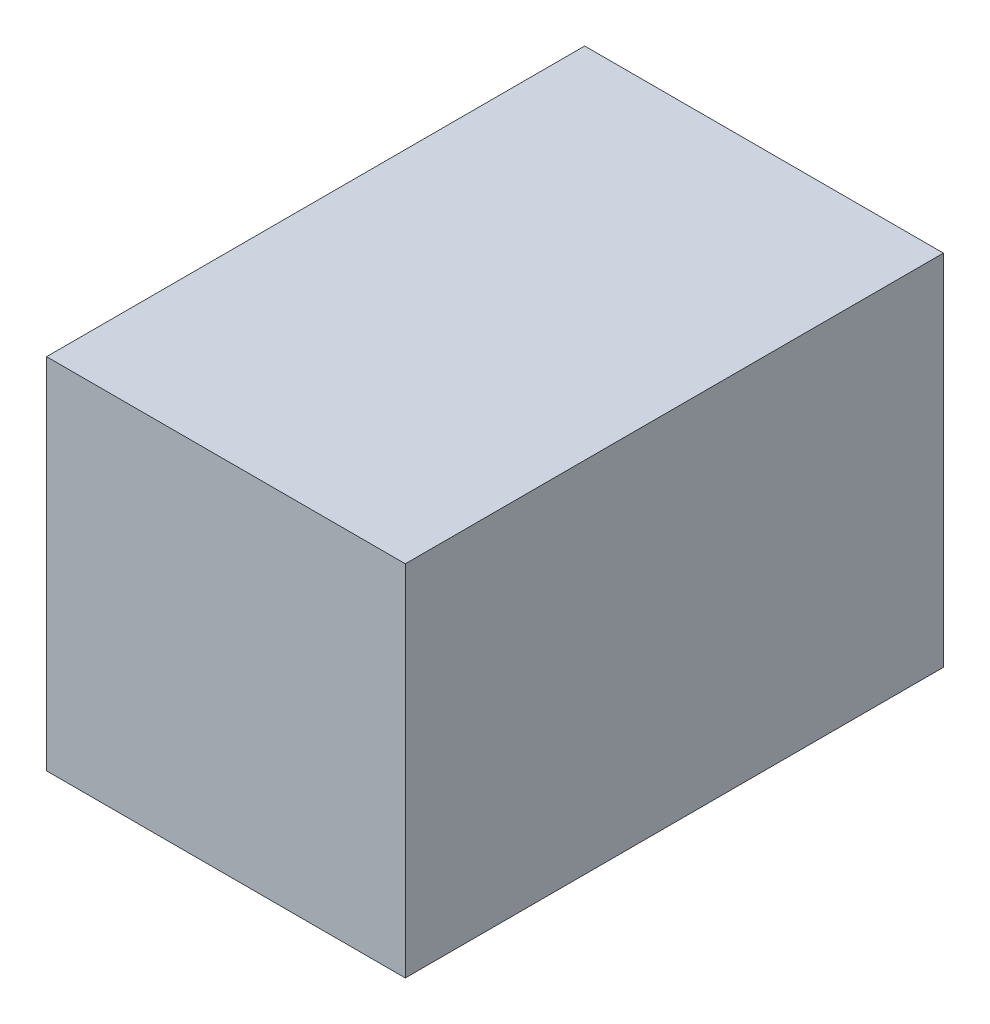
SolidWorks part; units mm, degrees
ref_plane "Front Plane" through (0, 0, 0) normal (0, 0, 1) x (1, 0, 0)
ref_plane "Top Plane" through (0, 0, 0) normal (0, 1, 0) x (1, 0, 0)
ref_plane "Right Plane" through (0, 0, 0) normal (1, 0, 0) x (0, 0, -1)
sketch "Sketch1" plane through (0, 0, 0) normal (0, 0, 1) x (1, 0, 0)
  line L1 (50.8, -50.8) -> (-50.8, -50.8)
  line L2 (50.8, -50.8) -> (50.8, 50.8)
  line L3 (50.8, 50.8) -> (-50.8, 50.8)
  line L4 (-50.8, -50.8) -> (-50.8, 50.8)
  line L5 (50.8, -50.8) -> (-50.8, 50.8) construction
  line L6 (50.8, 50.8) -> (-50.8, -50.8) construction
  point P0 (0, 0)
  dimension "D1" = 101.6
  dimension "D2" = 101.6
extrude "Boss-Extrude1" add sketch "Sketch1" along normal blind 152.4
